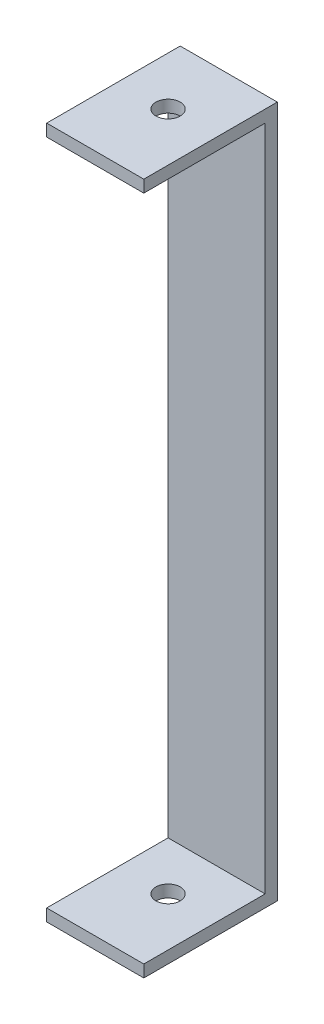
SolidWorks part; units mm, degrees
ref_plane "Front Plane" through (0, 0, 0) normal (0, 0, 1) x (1, 0, 0)
ref_plane "Top Plane" through (0, 0, 0) normal (0, 1, 0) x (1, 0, 0)
ref_plane "Right Plane" through (0, 0, 0) normal (1, 0, 0) x (0, 0, -1)
sketch "Sketch1" plane through (0, 0, 0) normal (0, 0, 1) x (1, 0, 0)
  line L1 (0.3404, 0.1702) -> (16.3404, 0.1702)
  line L2 (0.3404, 0.1702) -> (0.3404, 114.1702)
  line L3 (0.3404, 114.1702) -> (16.3404, 114.1702)
  line L4 (16.3404, 0.1702) -> (16.3404, 114.1702)
  dimension "D1" = 16
  dimension "D2" = 114
extrude "Boss-Extrude2" add sketch "Sketch1" along normal blind 2
sketch "Sketch2" plane through (0, 0, 2) normal (0, 0, 1) x (1, 0, 0)
  line L0 (16.3404, 114.1702) -> (0.3404, 114.1702) construction
  line L1 (16.3404, 114.1702) -> (0.3404, 114.1702)
  line L2 (16.3404, 114.1702) -> (16.3404, 112.1702)
  line L3 (16.3404, 112.1702) -> (0.3404, 112.1702)
  line L4 (0.3404, 114.1702) -> (0.3404, 112.1702)
  line L5 (0.3404, 114.1702) -> (0.3404, 0.1702) construction
  line L6 (16.3404, 0.1702) -> (16.3404, 114.1702) construction
  dimension "D1" = 0
  dimension "D2" = 0
  dimension "D3" = 0
  dimension "D4" = 2
extrude "Boss-Extrude3" add sketch "Sketch2" along normal blind 20
sketch "Sketch3" plane through (0, 0, 2) normal (0, 0, 1) x (1, 0, 0)
  line L0 (0.3404, 0.1702) -> (16.3404, 0.1702) construction
  line L1 (16.3404, 2.1702) -> (0.3404, 2.1702)
  line L2 (16.3404, 2.1702) -> (16.3404, 0.1702)
  line L3 (16.3404, 0.1702) -> (0.3404, 0.1702)
  line L4 (0.3404, 2.1702) -> (0.3404, 0.1702)
  line L5 (0.3404, 112.1702) -> (0.3404, 0.1702) construction
  line L6 (16.3404, 0.1702) -> (16.3404, 112.1702) construction
  point P6 (0.3404, 1.1702)
  point P9 (16.3404, 1.1702)
  dimension "D1" = 0
  dimension "D2" = 0
  dimension "D3" = 0
  dimension "D4" = 2
extrude "Boss-Extrude4" add sketch "Sketch3" along normal blind 20
sketch "Sketch4" plane through (0, 114.1702, 0) normal (0, 1, 0) x (1, 0, 0)
  line L0 (0.3404, -22) -> (0.3404, 0) construction
  line L1 (16.3404, 0) -> (0.3404, 0) construction
  circle A0 centre (8.3404, -10) radius 2
  dimension "D3" = 4
  dimension "D1" = 8
  dimension "D2" = 10
extrude "Cut-Extrude2" cut sketch "Sketch4" against normal through all
